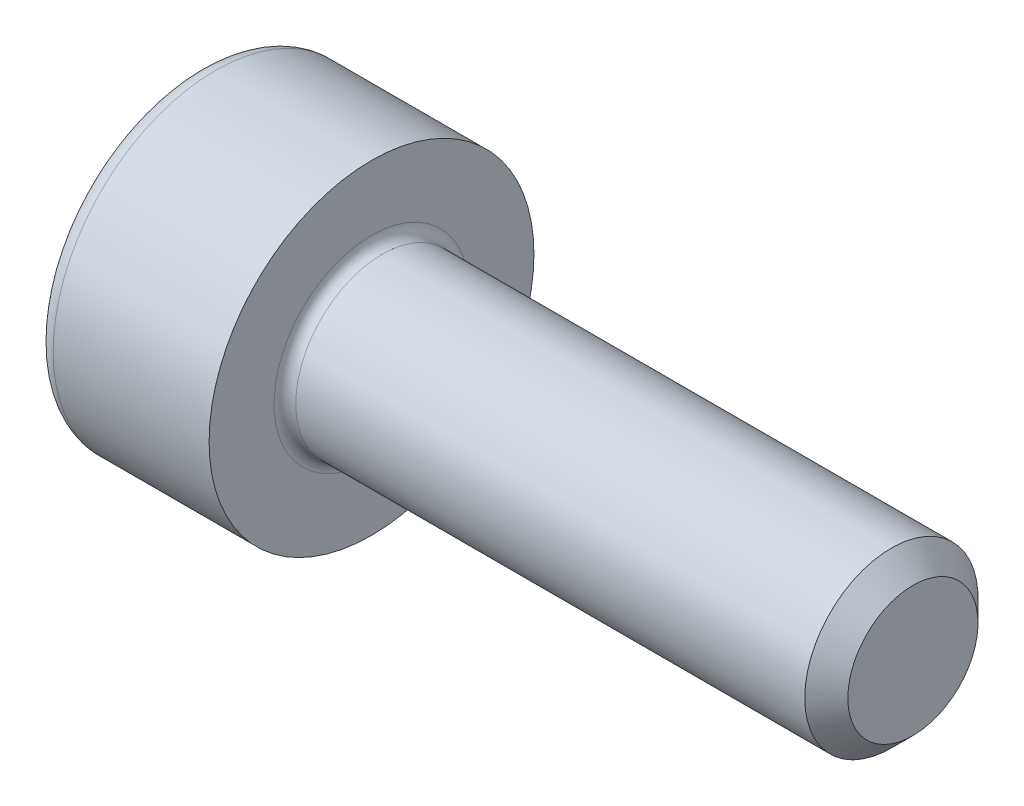
SolidWorks part; units mm, degrees
revolve "Base-Revolve" add sketch "BodySke"
sketch "BodySke" plane through (0, 0, 0) normal (0, 0, 1) x (1, 0, 0)
  line L0 (0, 0) -> (0, 1.5)
  line L1 (0, 1.5) -> (1.6, 1.5)
  line L2 (1.6, 1.5) -> (1.6, 0.8)
  line L3 (1.6, 0.8) -> (6.401, 0.8)
  line L4 (6.6, 0.601) -> (6.6, 0)
  line L5 (6.6, 0) -> (0, 0)
  line L6 (-31.75, 0) -> (127, 0) construction
  line L8 (6.6, 0.601) -> (6.401, 0.8)
  line L10 (6.6, -0.601) -> (6.401, -0.8) construction
  line L11 (1.95, 9.525) -> (1.95, 3.175) construction
  line L12 (1.6, 9.525) -> (1.6, 3.175) construction
  line L13 (-53.4, 9.525) -> (-53.4, 3.175) construction
  dimension "Head_ht" = 1.6
  dimension "Length" = 5
  dimension "Body_ch_ang" = 45
  dimension "Diameter" = 1.6
  dimension "Minor_dia" = 1.202
  dimension "Advance" = 0.35
  dimension "Thread_nom" = 5
  dimension "Thread_length" = 60
  dimension "Head_dia" = 3
cosmetic thread "ThreadCosmetic" [suppressed]
fillet "Fillet1" radius 0.1 1 edges at (1.6, 0, 0.8)
fillet "Fillet2" radius 0.16 1 edges at (0, 0, 1.5)
ref_plane "Plane1" through (0, 0, 0) normal (0, 0, 1) x (1, 0, 0)
ref_plane "Plane2" through (0, 0, 0) normal (0, 1, 0) x (1, 0, 0)
ref_plane "Plane3" through (0, 0, 0) normal (1, 0, 0) x (0, 0, -1)
sketch "Sketch2" plane through (0, 0, 0) normal (0, 0, 1) x (1, 0, 0)
  line L0 (0, 0.76) -> (0.7, 0.76)
  line L1 (0.7, 0.76) -> (1.1388, 0)
  line L2 (-31.75, 0) -> (127, 0) construction
  line L3 (1.1388, 0) -> (0, 0)
  line L4 (0, 0) -> (0, 0.76)
  line L6 (0, 0) -> (47.625, 0) construction
  dimension "D1" = 0.76
  dimension "D2" = 60
  dimension "Depth" = 0.7
revolve "Hex-PreBroach" cut sketch "Sketch2" angle 360 about L6
sketch "Sketch3" plane through (0, 0, 0) normal (-1, 0, 0) x (0, 0.5, 0.866)
  line L0 (0.4388, 0.76) -> (-0.4388, 0.76)
  line L1 (-0.4388, 0.76) -> (-0.8776, 0)
  line L2 (0.4388, 0.76) -> (0.8776, 0)
  line L3 (0.4388, -0.76) -> (0.8776, 0)
  line L4 (0.4388, -0.76) -> (-0.4388, -0.76)
  line L5 (-0.4388, -0.76) -> (-0.8776, 0)
  dimension "D1" = 0.76
  dimension "D2" = 0.76
  dimension "Hex_size" = 1.52
extrude "Hex" cut sketch "Sketch3" against normal blind 0.7
sketch "ThdSchSke" plane through (0, 0, 0) normal (0, 0, 1) x (1, 0, 0)
  line L0 (2.65, -0.601) -> (2.5107, -0.8)
  line L1 (2.65, -0.601) -> (2.7893, -0.8)
  line L2 (2.7893, -0.8) -> (2.7893, -1)
  line L3 (-3.175, 0) -> (5.1513, 0) construction
  line L4 (0, 1.34) -> (0, -1.34) construction
  line L5 (2.7893, -1) -> (2.5107, -1)
  line L6 (2.5107, -1) -> (2.5107, -0.8)
  dimension "Thread_minor" = 1.202
  dimension "Diameter" = 1.6
  dimension "Start" = 2.65
revolve "ThreadSchematic" [suppressed] cut sketch "ThdSchSke" angle 360 about L3
pattern_linear "ThdSchPat" [suppressed]
equation "\"D2@Sketch3\" = \"Hex_size@Sketch3\" / 2"
equation "\"D1@Sketch3\" = \"Hex_size@Sketch3\" / 2"
equation "\"D1@Sketch2\" = \"Hex_size@Sketch3\" / 2"
equation "\"Thread_minor@ThreadCosmetic\"  =  \"Minor_dia@BodySke\""
equation "\"Depth@Sketch2\" =  \"Key_eng@Hex\""
equation "\"Thread_length@ThreadCosmetic\" = ((sgn( (\"Length@BodySke\" - \"Advance@BodySke\" * 3.0) - \"Thread_nom@BodySke\" )-1)*( (\"Length@BodySke\" - \"Advance@BodySke\" * 3.0) - \"Thread_nom@BodySke\" ))/-2+ \"Thread_nom@BodySke\""
equation "\"Thread_minor@ThdSchSke\" = \"Minor_dia@BodySke\""
equation "\"Diameter@ThdSchSke\" = \"Diameter@BodySke\""
equation "\"Overcut@ThdSchSke\" = \"Diameter@BodySke\" * 1.25"
equation "\"Start@ThdSchSke\" = \"Head_ht@BodySke\" + \"Length@BodySke\" - \"Thread_length@ThreadCosmetic\"  '---Non-countersunk---"
equation "\"Num_threads@ThdSchPat\" = int( \"Thread_length@ThreadCosmetic\" / \"Advance@BodySke\" + 0.999 )  + 1"
equation "\"Advance@ThdSchPat\" = \"Thread_length@ThreadCosmetic\" /  (\"Num_threads@ThdSchPat\" - 1) 'relax it"
equation "\"Num_threads@ThdSchPat\" = \"Num_threads@ThdSchPat\" - sgn( \"Num_threads@ThdSchPat\" - 1) '---chamfered tips only---"
